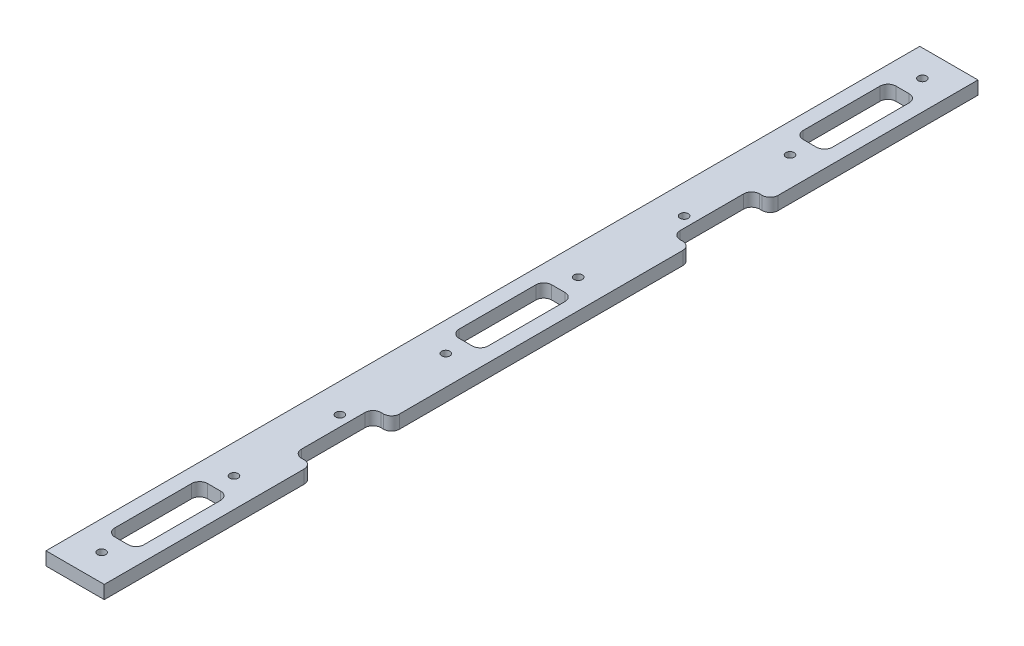
SolidWorks part; units mm, degrees
material "Thornel Mat VMA"
ref_plane "前视基准面" through (0, 0, 0) normal (0, 0, 1) x (1, 0, 0)
ref_plane "上视基准面" through (0, 0, 0) normal (0, 1, 0) x (1, 0, 0)
ref_plane "右视基准面" through (0, 0, 0) normal (1, 0, 0) x (0, 0, -1)
sketch "草图1" plane through (0, 0, 0) normal (0, 1, 0) x (1, 0, 0)
  line L0 (0, -165) -> (0, 165) construction
  line L1 (-11, -165) -> (11, -165)
  line L2 (-11, -165) -> (-11, 165)
  line L3 (-11, 165) -> (11, 165)
  line L4 (11, -165) -> (11, 165)
  line L5 (-11, -165) -> (11, 165) construction
  line L6 (-11, 165) -> (11, -165) construction
  line L7 (-11, 0) -> (11, 0) construction
  circle A0 centre (0, 25) radius 1.55
  circle A1 centre (0, 65) radius 1.55
  circle A2 centre (0, -25) radius 1.55
  circle A3 centre (0, -65) radius 1.55
  circle A4 centre (0, 105) radius 1.55
  circle A5 centre (0, 155) radius 1.55
  circle A6 centre (0, -155) radius 1.55
  circle A7 centre (0, -105) radius 1.55
  point P0 (0, 0)
  dimension "D3" = 3.1
  dimension "D4" = 25
  dimension "D1" = 330
  dimension "D2" = 22
  dimension "D5" = 2
  dimension "D6" = 2
  dimension "D7" = 2
extrude "凸台-拉伸1" add sketch "草图1" along normal blind 5
sketch "草图2" plane through (0, 5, 0) normal (0, 1, 0) x (1, 0, 0)
  line L0 (-11, 0) -> (142.3408, 0) construction
  line L1 (-11, 165) -> (-11, -165) construction
  line L2 (11, -165) -> (11, 165) construction
  line L3 (4, 56.5) -> (18, 56.5)
  line L4 (4, 56.5) -> (4, 86.5)
  line L5 (4, 86.5) -> (18, 86.5)
  line L6 (18, 56.5) -> (18, 86.5)
  line L7 (4, 56.5) -> (18, 86.5) construction
  line L8 (4, 86.5) -> (18, 56.5) construction
  line L9 (4, -86.5) -> (18, -86.5)
  line L10 (18, -56.5) -> (18, -86.5)
  line L11 (4, -56.5) -> (18, -56.5)
  line L12 (4, -56.5) -> (4, -86.5)
  point P5 (11, 71.5)
  dimension "D1" = 56.5
  dimension "D2" = 30
  dimension "D3" = 14
extrude "切除-拉伸1" cut sketch "草图2" against normal through all
fillet "圆角1" radius 3 8 edges at (11, 2.5, 86.5) (4, 2.5, 86.5) (11, 2.5, 56.5) (4, 2.5, 56.5) (11, 2.5, -56.5) (11, 2.5, -86.5) (4, 2.5, -56.5) (4, 2.5, -86.5)
sketch "草图3" plane through (0, 5, 0) normal (0, 1, 0) x (1, 0, 0)
  line L0 (0, 155) -> (0, 105) construction
  line L1 (-11, 0) -> (11, 0) construction
  line L2 (-5.5, 112.5) -> (5.5, 112.5)
  line L3 (-5.5, 112.5) -> (-5.5, 147.5)
  line L4 (-5.5, 147.5) -> (5.5, 147.5)
  line L5 (5.5, 112.5) -> (5.5, 147.5)
  line L6 (-5.5, 112.5) -> (5.5, 147.5) construction
  line L7 (-5.5, 147.5) -> (5.5, 112.5) construction
  line L8 (-11, 165) -> (-11, -165) construction
  line L9 (11, -53.5) -> (11, 53.5) construction
  line L10 (-5.5, -147.5) -> (5.5, -147.5)
  line L11 (-5.5, -112.5) -> (5.5, -112.5)
  line L12 (-5.5, -112.5) -> (-5.5, -147.5)
  line L13 (5.5, -112.5) -> (5.5, -147.5)
  line L15 (-5.5, -17.5) -> (5.5, -17.5)
  line L16 (-5.5, -17.5) -> (-5.5, 17.5)
  line L17 (-5.5, 17.5) -> (5.5, 17.5)
  line L18 (5.5, -17.5) -> (5.5, 17.5)
  line L19 (-5.5, -17.5) -> (5.5, 17.5) construction
  line L20 (-5.5, 17.5) -> (5.5, -17.5) construction
  point P4 (0, 130)
  point P19 (0, 0)
  dimension "D1" = 35
  dimension "D2" = 11
  dimension "D3" = 35
  dimension "D4" = 11
extrude "切除-拉伸2" cut sketch "草图3" against normal through all
fillet "圆角2" radius 3 12 edges at (5.5, 2.5, 147.5) (-5.5, 2.5, 147.5) (-5.5, 2.5, 112.5) (5.5, 2.5, 112.5) (5.5, 2.5, 17.5) (-5.5, 2.5, 17.5) (5.5, 2.5, -17.5) (-5.5, 2.5, -17.5) (5.5, 2.5, -112.5) (-5.5, 2.5, -112.5) (5.5, 2.5, -147.5) (-5.5, 2.5, -147.5)
